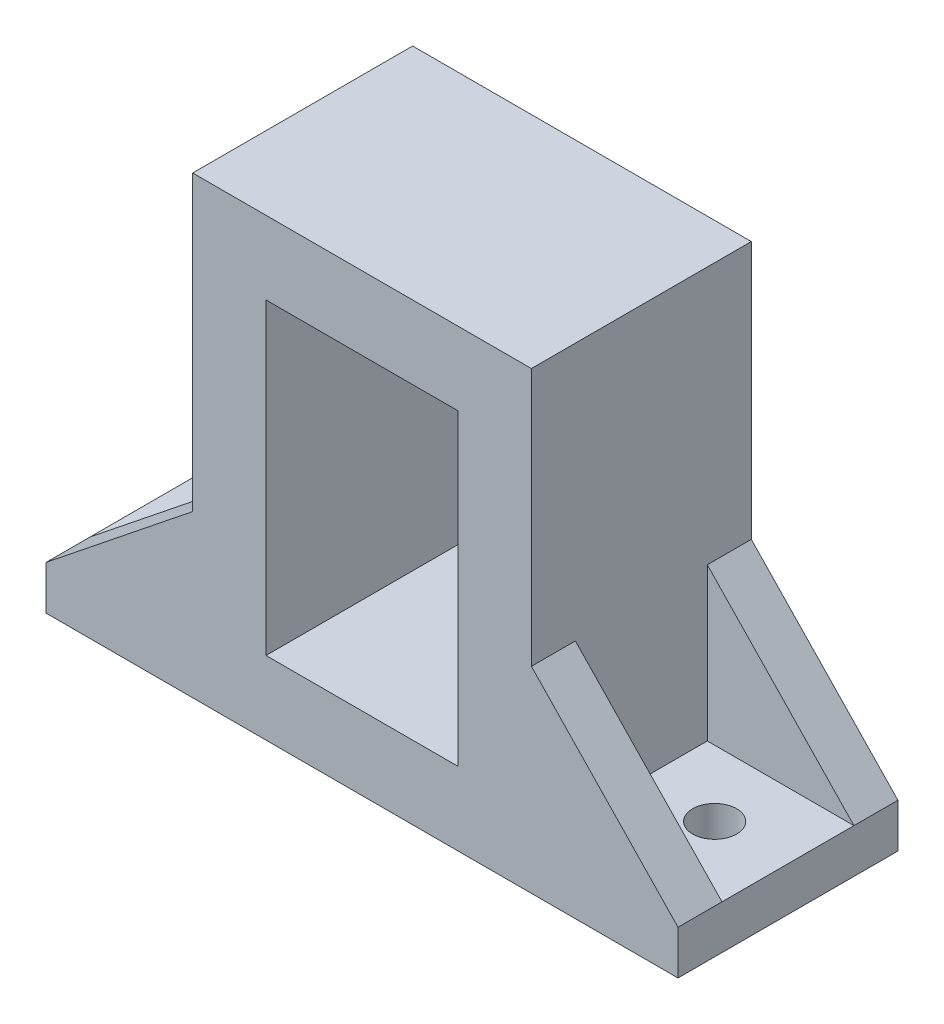
SolidWorks part; units mm, degrees
ref_plane "Plano frontal" through (0, 0, 0) normal (0, 0, 1) x (1, 0, 0)
ref_plane "Plano superior" through (0, 0, 0) normal (0, 1, 0) x (1, 0, 0)
ref_plane "Plano direito" through (0, 0, 0) normal (1, 0, 0) x (0, 0, -1)
sketch "Esboço1" plane through (0, 0, 0) normal (0, 0, 1) x (1, 0, 0)
  line L0 (0, 0) -> (-13.1, 0)
  line L1 (-13.1, 0) -> (-13.1, 21)
  line L2 (-13.1, 21) -> (0, 21)
  line L5 (0, 26) -> (5, 26)
  line L7 (5, 26) -> (5, -5)
  line L8 (-18.1, 0) -> (-18.1, 26)
  line L9 (0, 26) -> (-18.1, 26)
  line L10 (-18.1, 0) -> (-18.1, -5)
  line L11 (-18.1, -5) -> (5, -5)
  line L12 (0, 21) -> (0, 0)
extrude "Ressalto-extrusão1" add sketch "Esboço1" along normal blind 15
sketch "Esboço2" plane through (-18.1, 0, 0) normal (-1, 0, 0) x (0, 0, 1)
  line L0 (0, -5) -> (0, -2)
  line L1 (0, 26) -> (0, -5) construction
  line L2 (0, -2) -> (15, -2)
  line L3 (0, -5) -> (15, -5)
  line L4 (15, -5) -> (15, -2)
extrude "Ressalto-extrusão2" add sketch "Esboço2" along normal blind 10
sketch "Esboço3" plane through (-18.1, 0, 0) normal (-1, 0, 0) x (0, 0, 1)
  line L0 (0, -2) -> (0, 6)
  line L1 (0, 26) -> (0, -2) construction
  line L2 (0, 6) -> (3, 6)
  line L3 (15, 6) -> (12, 6)
  line L4 (15, -2) -> (15, 6)
  line L6 (3, 6) -> (3, -2)
  line L7 (12, 6) -> (12, -2)
  line L8 (0, -2) -> (3, -2)
  line L10 (12, -2) -> (15, -2)
extrude "Ressalto-extrusão3" add sketch "Esboço3" along normal blind 10
sketch "Esboço4" plane through (0, 0, 0) normal (0, 0, -1) x (-1, 0, 0)
  line L4 (18.1, 6) -> (28.1, -2)
  line L6 (28.1, -2) -> (28.1, 6)
  line L7 (18.1, 6) -> (28.1, 6)
extrude "Corte-extrusão1" cut sketch "Esboço4" against normal blind 19
sketch "Esboço5" plane through (0, -2, 0) normal (0, 1, 0) x (1, 0, 0)
  circle A0 centre (-23.1, -7.5) radius 1.5
extrude "Corte-extrusão2" cut sketch "Esboço5" against normal blind 19 contours A0
sketch "Esboço6" plane through (5, 0, 0) normal (1, 0, 0) x (0, 0, -1)
  line L0 (-15, -5) -> (-15, 8.4093)
  line L1 (-15, -5) -> (-15, 26) construction
  line L2 (-15, 8.4093) -> (-12, 8.4093)
  line L3 (0, -5) -> (0, 26) construction
  line L4 (-15, -5) -> (0, -5)
  line L5 (0, 8.4093) -> (0, -5)
  line L7 (-3, 8.4093) -> (0, 8.4093)
  line L8 (-12, 8.4093) -> (-12, -2)
  line L11 (-12, -2) -> (-3, -2)
  line L14 (-3, 8.4093) -> (-3, -2)
extrude "Ressalto-extrusão4" add sketch "Esboço6" along normal blind 10
sketch "Esboço7" plane through (0, 0, 0) normal (0, 0, -1) x (-1, 0, 0)
  line L0 (-5, 8.4093) -> (-15, -2)
  line L3 (-15, -2) -> (-15, 8.4093)
  line L4 (-15, 8.4093) -> (-5, 8.4093)
extrude "Corte-extrusão3" cut sketch "Esboço7" against normal blind 23
sketch "Esboço8" plane through (0, -2, 0) normal (0, 1, 0) x (1, 0, 0)
  circle A0 centre (10, -7.5) radius 1.5
extrude "Corte-extrusão4" cut sketch "Esboço8" against normal blind 23
